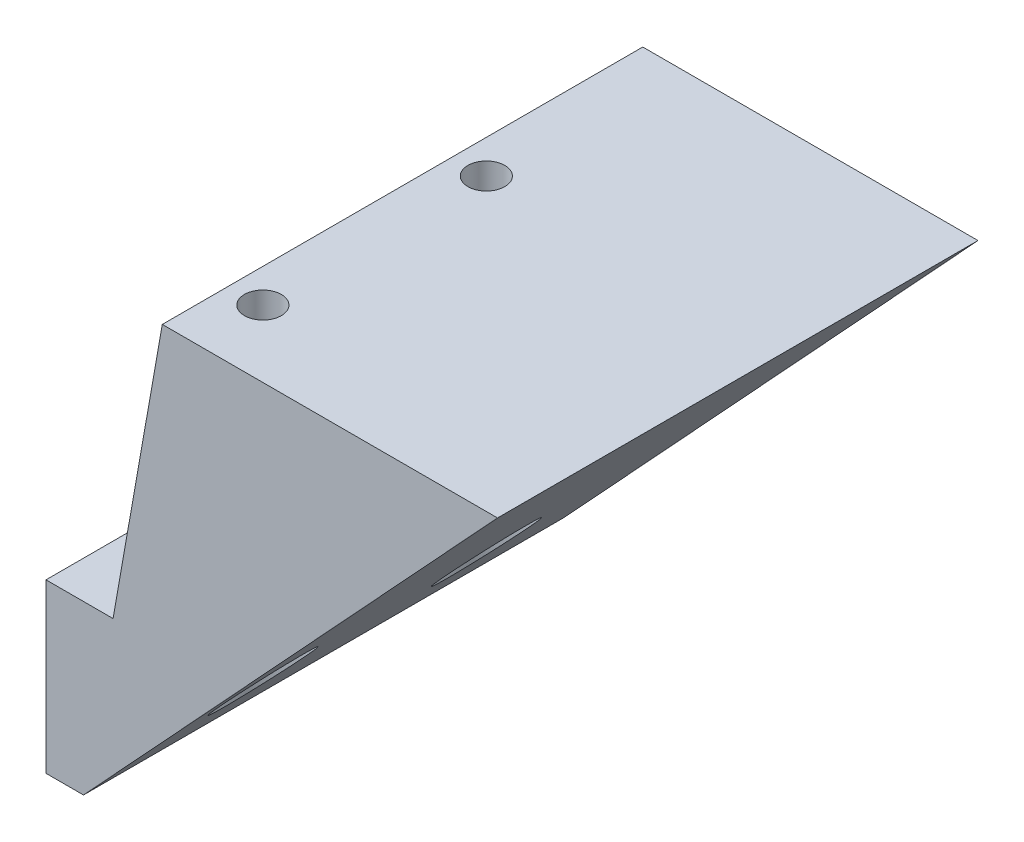
SolidWorks part; units mm, degrees
ref_plane "前视基准面" through (0, 0, 0) normal (0, 0, 1) x (1, 0, 0)
ref_plane "上视基准面" through (0, 0, 0) normal (0, 1, 0) x (1, 0, 0)
ref_plane "右视基准面" through (0, 0, 0) normal (1, 0, 0) x (0, 0, -1)
other "Configuration Table"
sketch "草图1" plane through (0, 0, 0) normal (0, 0, 1) x (1, 0, 0)
  line L0 (0, 0) -> (7.0531, 40)
  line L1 (7.0531, 40) -> (37.0531, 40)
  line L2 (37.0531, 40) -> (0, 0)
  dimension "D1" = 100
  dimension "D2" = 30
  dimension "D3" = 40
extrude "凸台-拉伸1" add sketch "草图1" along normal blind 43
sketch "草图2" plane through (0, 40, 0) normal (0, 1, 0) x (1, 0, 0)
  line L0 (37.0531, 0) -> (7.0531, 0) construction
  line L1 (7.0531, -43) -> (7.0531, 0) construction
  circle A0 centre (10.0531, -17) radius 1.65
  circle A1 centre (10.0531, -37) radius 1.65
  dimension "D1" = 3.3
  dimension "D2" = 20
  dimension "D3" = 17
  dimension "D4" = 3
extrude "切除-拉伸1" cut sketch "草图2" against normal blind 40
sketch "草图3" plane through (0, 0, 43) normal (0, 0, 1) x (1, 0, 0)
  line L0 (2.6449, 15) -> (-3.3551, 15)
  line L1 (7.0531, 40) -> (0, 0) construction
  line L2 (-3.3551, 15) -> (-3.3551, 0)
  line L3 (-3.3551, 0) -> (0, 0)
  line L4 (2.6449, 15) -> (0, 0)
  dimension "D1" = 6
  dimension "D2" = 15
extrude "凸台-拉伸2" add sketch "草图3" against normal blind 43
sketch "草图4" plane through (0, 0, 0) normal (0, -1, 0) x (1, 0, 0)
  circle A0 centre (10.0531, 37) radius 3.5
  circle A1 centre (10.0531, 17) radius 3.5
  dimension "D1" = 7
  dimension "D2" = 7
extrude "切除-拉伸2" cut sketch "草图4" against normal blind 15
